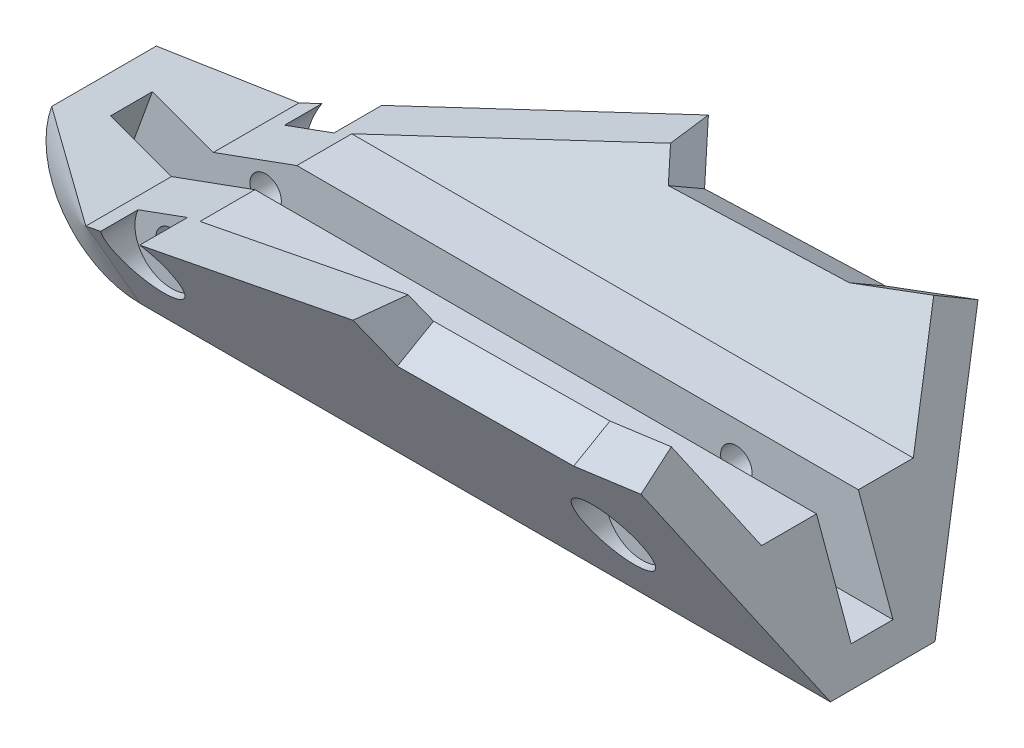
SolidWorks part; units mm, degrees
ref_plane "前视基准面" through (0, 0, 0) normal (0, 0, 1) x (1, 0, 0)
ref_plane "上视基准面" through (0, 0, 0) normal (0, 1, 0) x (1, 0, 0)
ref_plane "右视基准面" through (0, 0, 0) normal (1, 0, 0) x (0, 0, -1)
other "Configuration Table"
sketch "草图1" plane through (0, 0, 0) normal (1, 0, 0) x (0, 0, -1)
  line L0 (0, 0) -> (0, 34.4521) construction
  line L1 (5, 0) -> (-5, 0)
  line L2 (5, 0) -> (25, 34.641)
  line L3 (25, 34.641) -> (21.5359, 36.641)
  line L4 (21.5359, 36.641) -> (7.2539, 11.9038)
  line L5 (2, 2.8038) -> (-2, 2.8038)
  line L6 (2, 2.8038) -> (2, 11.9038)
  line L7 (2, 11.9038) -> (7.2539, 11.9038)
  line L8 (7.2539, 11.9038) -> (2, 2.8038) construction
  line L9 (-2, 2.8038) -> (-2, 11.9038)
  line L10 (-2, 11.9038) -> (-7.2539, 11.9038)
  line L11 (-25, 34.641) -> (-21.5359, 36.641)
  line L12 (-5, 0) -> (-25, 34.641)
  line L13 (-21.5359, 36.641) -> (-7.2539, 11.9038)
  point P6 (0, 0)
  point P13 (0, 2.8038)
  dimension "D1" = 4
  dimension "D2" = 2
  dimension "D3" = 5
  dimension "D4" = 40
  dimension "D5" = 30
  dimension "D6" = 9.1
extrude "凸台-拉伸1" add sketch "草图1" along normal blind 66
sketch "草图2" plane through (0, 0, 0) normal (0, 0, 1) x (1, 0, 0)
  line L0 (0, 9) -> (0, 36.641)
  line L1 (0, 34.641) -> (0, 0) construction
  line L2 (0, 36.641) -> (75.9431, 36.641)
  line L3 (75.9431, 36.641) -> (66, 33.022)
  line L4 (0, 8.23) -> (66, 8.23) construction
  line L5 (66, 0) -> (0, 0) construction
  line L6 (55.3869, 29.1592) -> (66, 0)
  line L7 (66, 0) -> (66, 33.022)
  line L8 (55.3869, 29.1592) -> (0, 9)
  circle A0 centre (5, 8.23) radius 1.5
  circle A1 centre (50, 8.23) radius 1.5
  point P8 (66, 5)
  point P9 (0, 6.4606)
  point P18 (0, 0)
  dimension "D5" = 5
  dimension "D6" = 3
  dimension "D7" = 3
  dimension "D1" = 70
  dimension "D2" = 9
  dimension "D3" = 8.23
  dimension "D4" = 45
extrude "切除-拉伸1" cut sketch "草图2" against normal blind 66 and the other way blind 66
ref_plane "基准面2" through (0, 0, 12) normal (0, 0, -1) x (-1, 0, 0)
sketch "草图4" plane through (0, 0, 12) normal (0, 0, -1) x (-1, 0, 0)
  circle A0 centre (-5, 8.23) radius 3.5
  circle A1 centre (-50, 8.23) radius 3.5
  dimension "D1" = 7
  dimension "D2" = 7
extrude "切除-拉伸2" cut sketch "草图4" along normal blind 5
mirror "镜向1" about plane through (0, 0, 0) normal (0, 0, 1) of "切除-拉伸2"
sketch "草图5" plane through (0, -2.1651, 3.75) normal (0, -0.5, 0.866) x (1, 0, 0)
  line L0 (32.3396, 26.4839) -> (34.2769, 21.8744)
  line L1 (6.5313, 15.6373) -> (55.3869, 36.1701) construction
  line L2 (34.2769, 21.8744) -> (51.3645, 22.3202)
  line L3 (51.3645, 22.3202) -> (58.9944, 24.7252)
  line L4 (55.3869, 36.1701) -> (66, 2.5) construction
  line L5 (58.9944, 24.7252) -> (55.3869, 36.1701)
  line L6 (55.3869, 36.1701) -> (32.3396, 26.4839)
  dimension "D1" = 25
  dimension "D2" = 12
  dimension "D3" = 8
  dimension "D4" = 5
extrude "切除-拉伸3" cut sketch "草图5" against normal blind 66
mirror "镜向2" about plane through (0, 0, 0) normal (0, 0, 1) of "切除-拉伸3"
sketch "草图6" plane through (0, 0, 0) normal (-1, 0, 0) x (0, 0, 1)
  line L0 (-10.1962, 9) -> (-2, 9)
  line L1 (-2, 9) -> (-2, 2.8038)
  line L2 (-2, 2.8038) -> (2, 2.8038)
  line L3 (2, 2.8038) -> (2, 9)
  line L4 (2, 9) -> (10.1962, 9)
  line L5 (10.1962, 9) -> (5, 0)
  line L6 (5, 0) -> (-5, 0)
  line L7 (-5, 0) -> (-10.1962, 9)
revolve "旋转1" add sketch "草图6" angle 110 about L0
sketch "草图7" plane through (2.8925, 7.9472, 0) normal (0.342, 0.9397, 0) x (0.9397, -0.342, 0)
  line L1 (-9.2743, 2) -> (-3.0782, 2)
  line L2 (-9.2743, 2) -> (-9.2743, -2)
  line L3 (-9.2743, -2) -> (-3.0782, -2)
  line L4 (-3.0782, 2) -> (-3.0782, -2)
extrude "切除-拉伸4" cut sketch "草图7" against normal blind 66
